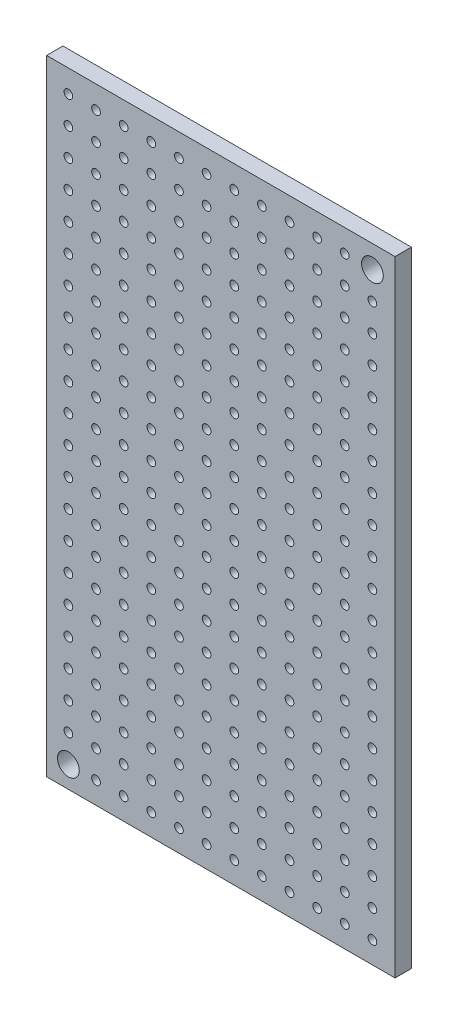
SolidWorks part; units mm, degrees
ref_plane "Front Plane" through (0, 0, 0) normal (0, 0, 1) x (1, 0, 0)
ref_plane "Top Plane" through (0, 0, 0) normal (0, 1, 0) x (1, 0, 0)
ref_plane "Right Plane" through (0, 0, 0) normal (1, 0, 0) x (0, 0, -1)
sketch "Sketch1" plane through (0, 0, 0) normal (0, 0, 1) x (1, 0, 0)
  line L1 (0, 0) -> (32.02, 0)
  line L2 (0, 0) -> (0, 57.42)
  line L3 (0, 57.42) -> (32.02, 57.42)
  line L4 (32.02, 0) -> (32.02, 57.42)
  circle A0 centre (2, 2) radius 0.4
  circle A1 centre (4.54, 2) radius 0.4
  circle A2 centre (7.08, 2) radius 0.4
  circle A3 centre (9.62, 2) radius 0.4
  circle A4 centre (12.16, 2) radius 0.4
  circle A5 centre (14.7, 2) radius 0.4
  circle A6 centre (17.24, 2) radius 0.4
  circle A7 centre (19.78, 2) radius 0.4
  circle A8 centre (22.32, 2) radius 0.4
  circle A9 centre (24.86, 2) radius 0.4
  circle A10 centre (27.4, 2) radius 0.4
  circle A11 centre (29.94, 2) radius 0.4
  circle A12 centre (2, 4.54) radius 0.4
  circle A13 centre (4.54, 4.54) radius 0.4
  circle A14 centre (7.08, 4.54) radius 0.4
  circle A15 centre (9.62, 4.54) radius 0.4
  circle A16 centre (12.16, 4.54) radius 0.4
  circle A17 centre (14.7, 4.54) radius 0.4
  circle A18 centre (17.24, 4.54) radius 0.4
  circle A19 centre (19.78, 4.54) radius 0.4
  circle A20 centre (22.32, 4.54) radius 0.4
  circle A21 centre (24.86, 4.54) radius 0.4
  circle A22 centre (27.4, 4.54) radius 0.4
  circle A23 centre (29.94, 4.54) radius 0.4
  circle A24 centre (2, 7.08) radius 0.4
  circle A25 centre (4.54, 7.08) radius 0.4
  circle A26 centre (7.08, 7.08) radius 0.4
  circle A27 centre (9.62, 7.08) radius 0.4
  circle A28 centre (12.16, 7.08) radius 0.4
  circle A29 centre (14.7, 7.08) radius 0.4
  circle A30 centre (17.24, 7.08) radius 0.4
  circle A31 centre (19.78, 7.08) radius 0.4
  circle A32 centre (22.32, 7.08) radius 0.4
  circle A33 centre (24.86, 7.08) radius 0.4
  circle A34 centre (27.4, 7.08) radius 0.4
  circle A35 centre (29.94, 7.08) radius 0.4
  circle A36 centre (2, 9.62) radius 0.4
  circle A37 centre (4.54, 9.62) radius 0.4
  circle A38 centre (7.08, 9.62) radius 0.4
  circle A39 centre (9.62, 9.62) radius 0.4
  circle A40 centre (12.16, 9.62) radius 0.4
  circle A41 centre (14.7, 9.62) radius 0.4
  circle A42 centre (17.24, 9.62) radius 0.4
  circle A43 centre (19.78, 9.62) radius 0.4
  circle A44 centre (22.32, 9.62) radius 0.4
  circle A45 centre (24.86, 9.62) radius 0.4
  circle A46 centre (27.4, 9.62) radius 0.4
  circle A47 centre (29.94, 9.62) radius 0.4
  circle A48 centre (2, 12.16) radius 0.4
  circle A49 centre (4.54, 12.16) radius 0.4
  circle A50 centre (7.08, 12.16) radius 0.4
  circle A51 centre (9.62, 12.16) radius 0.4
  circle A52 centre (12.16, 12.16) radius 0.4
  circle A53 centre (14.7, 12.16) radius 0.4
  circle A54 centre (17.24, 12.16) radius 0.4
  circle A55 centre (19.78, 12.16) radius 0.4
  circle A56 centre (22.32, 12.16) radius 0.4
  circle A57 centre (24.86, 12.16) radius 0.4
  circle A58 centre (27.4, 12.16) radius 0.4
  circle A59 centre (29.94, 12.16) radius 0.4
  circle A60 centre (2, 14.7) radius 0.4
  circle A61 centre (4.54, 14.7) radius 0.4
  circle A62 centre (7.08, 14.7) radius 0.4
  circle A63 centre (9.62, 14.7) radius 0.4
  circle A64 centre (12.16, 14.7) radius 0.4
  circle A65 centre (14.7, 14.7) radius 0.4
  circle A66 centre (17.24, 14.7) radius 0.4
  circle A67 centre (19.78, 14.7) radius 0.4
  circle A68 centre (22.32, 14.7) radius 0.4
  circle A69 centre (24.86, 14.7) radius 0.4
  circle A70 centre (27.4, 14.7) radius 0.4
  circle A71 centre (29.94, 14.7) radius 0.4
  circle A72 centre (2, 17.24) radius 0.4
  circle A73 centre (4.54, 17.24) radius 0.4
  circle A74 centre (7.08, 17.24) radius 0.4
  circle A75 centre (9.62, 17.24) radius 0.4
  circle A76 centre (12.16, 17.24) radius 0.4
  circle A77 centre (14.7, 17.24) radius 0.4
  circle A78 centre (17.24, 17.24) radius 0.4
  circle A79 centre (19.78, 17.24) radius 0.4
  circle A80 centre (22.32, 17.24) radius 0.4
  circle A81 centre (24.86, 17.24) radius 0.4
  circle A82 centre (27.4, 17.24) radius 0.4
  circle A83 centre (29.94, 17.24) radius 0.4
  circle A84 centre (2, 19.78) radius 0.4
  circle A85 centre (4.54, 19.78) radius 0.4
  circle A86 centre (7.08, 19.78) radius 0.4
  circle A87 centre (9.62, 19.78) radius 0.4
  circle A88 centre (12.16, 19.78) radius 0.4
  circle A89 centre (14.7, 19.78) radius 0.4
  circle A90 centre (17.24, 19.78) radius 0.4
  circle A91 centre (19.78, 19.78) radius 0.4
  circle A92 centre (22.32, 19.78) radius 0.4
  circle A93 centre (24.86, 19.78) radius 0.4
  circle A94 centre (27.4, 19.78) radius 0.4
  circle A95 centre (29.94, 19.78) radius 0.4
  circle A96 centre (2, 22.32) radius 0.4
  circle A97 centre (4.54, 22.32) radius 0.4
  circle A98 centre (7.08, 22.32) radius 0.4
  circle A99 centre (9.62, 22.32) radius 0.4
  circle A100 centre (12.16, 22.32) radius 0.4
  circle A101 centre (14.7, 22.32) radius 0.4
  circle A102 centre (17.24, 22.32) radius 0.4
  circle A103 centre (19.78, 22.32) radius 0.4
  circle A104 centre (22.32, 22.32) radius 0.4
  circle A105 centre (24.86, 22.32) radius 0.4
  circle A106 centre (27.4, 22.32) radius 0.4
  circle A107 centre (29.94, 22.32) radius 0.4
  circle A108 centre (2, 24.86) radius 0.4
  circle A109 centre (4.54, 24.86) radius 0.4
  circle A110 centre (7.08, 24.86) radius 0.4
  circle A111 centre (9.62, 24.86) radius 0.4
  circle A112 centre (12.16, 24.86) radius 0.4
  circle A113 centre (14.7, 24.86) radius 0.4
  circle A114 centre (17.24, 24.86) radius 0.4
  circle A115 centre (19.78, 24.86) radius 0.4
  circle A116 centre (22.32, 24.86) radius 0.4
  circle A117 centre (24.86, 24.86) radius 0.4
  circle A118 centre (27.4, 24.86) radius 0.4
  circle A119 centre (29.94, 24.86) radius 0.4
  circle A120 centre (2, 27.4) radius 0.4
  circle A121 centre (4.54, 27.4) radius 0.4
  circle A122 centre (7.08, 27.4) radius 0.4
  circle A123 centre (9.62, 27.4) radius 0.4
  circle A124 centre (12.16, 27.4) radius 0.4
  circle A125 centre (14.7, 27.4) radius 0.4
  circle A126 centre (17.24, 27.4) radius 0.4
  circle A127 centre (19.78, 27.4) radius 0.4
  circle A128 centre (22.32, 27.4) radius 0.4
  circle A129 centre (24.86, 27.4) radius 0.4
  circle A130 centre (27.4, 27.4) radius 0.4
  circle A131 centre (29.94, 27.4) radius 0.4
  circle A132 centre (2, 29.94) radius 0.4
  circle A133 centre (4.54, 29.94) radius 0.4
  circle A134 centre (7.08, 29.94) radius 0.4
  circle A135 centre (9.62, 29.94) radius 0.4
  circle A136 centre (12.16, 29.94) radius 0.4
  circle A137 centre (14.7, 29.94) radius 0.4
  circle A138 centre (17.24, 29.94) radius 0.4
  circle A139 centre (19.78, 29.94) radius 0.4
  circle A140 centre (22.32, 29.94) radius 0.4
  circle A141 centre (24.86, 29.94) radius 0.4
  circle A142 centre (27.4, 29.94) radius 0.4
  circle A143 centre (29.94, 29.94) radius 0.4
  circle A144 centre (2, 32.48) radius 0.4
  circle A145 centre (4.54, 32.48) radius 0.4
  circle A146 centre (7.08, 32.48) radius 0.4
  circle A147 centre (9.62, 32.48) radius 0.4
  circle A148 centre (12.16, 32.48) radius 0.4
  circle A149 centre (14.7, 32.48) radius 0.4
  circle A150 centre (17.24, 32.48) radius 0.4
  circle A151 centre (19.78, 32.48) radius 0.4
  circle A152 centre (22.32, 32.48) radius 0.4
  circle A153 centre (24.86, 32.48) radius 0.4
  circle A154 centre (27.4, 32.48) radius 0.4
  circle A155 centre (29.94, 32.48) radius 0.4
  circle A156 centre (2, 35.02) radius 0.4
  circle A157 centre (4.54, 35.02) radius 0.4
  circle A158 centre (7.08, 35.02) radius 0.4
  circle A159 centre (9.62, 35.02) radius 0.4
  circle A160 centre (12.16, 35.02) radius 0.4
  circle A161 centre (14.7, 35.02) radius 0.4
  circle A162 centre (17.24, 35.02) radius 0.4
  circle A163 centre (19.78, 35.02) radius 0.4
  circle A164 centre (22.32, 35.02) radius 0.4
  circle A165 centre (24.86, 35.02) radius 0.4
  circle A166 centre (27.4, 35.02) radius 0.4
  circle A167 centre (29.94, 35.02) radius 0.4
  circle A168 centre (2, 37.56) radius 0.4
  circle A169 centre (4.54, 37.56) radius 0.4
  circle A170 centre (7.08, 37.56) radius 0.4
  circle A171 centre (9.62, 37.56) radius 0.4
  circle A172 centre (12.16, 37.56) radius 0.4
  circle A173 centre (14.7, 37.56) radius 0.4
  circle A174 centre (17.24, 37.56) radius 0.4
  circle A175 centre (19.78, 37.56) radius 0.4
  circle A176 centre (22.32, 37.56) radius 0.4
  circle A177 centre (24.86, 37.56) radius 0.4
  circle A178 centre (27.4, 37.56) radius 0.4
  circle A179 centre (29.94, 37.56) radius 0.4
  circle A180 centre (2, 40.1) radius 0.4
  circle A181 centre (4.54, 40.1) radius 0.4
  circle A182 centre (7.08, 40.1) radius 0.4
  circle A183 centre (9.62, 40.1) radius 0.4
  circle A184 centre (12.16, 40.1) radius 0.4
  circle A185 centre (14.7, 40.1) radius 0.4
  circle A186 centre (17.24, 40.1) radius 0.4
  circle A187 centre (19.78, 40.1) radius 0.4
  circle A188 centre (22.32, 40.1) radius 0.4
  circle A189 centre (24.86, 40.1) radius 0.4
  circle A190 centre (27.4, 40.1) radius 0.4
  circle A191 centre (29.94, 40.1) radius 0.4
  circle A192 centre (2, 42.64) radius 0.4
  circle A193 centre (4.54, 42.64) radius 0.4
  circle A194 centre (7.08, 42.64) radius 0.4
  circle A195 centre (9.62, 42.64) radius 0.4
  circle A196 centre (12.16, 42.64) radius 0.4
  circle A197 centre (14.7, 42.64) radius 0.4
  circle A198 centre (17.24, 42.64) radius 0.4
  circle A199 centre (19.78, 42.64) radius 0.4
  circle A200 centre (22.32, 42.64) radius 0.4
  circle A201 centre (24.86, 42.64) radius 0.4
  circle A202 centre (27.4, 42.64) radius 0.4
  circle A203 centre (29.94, 42.64) radius 0.4
  circle A204 centre (2, 45.18) radius 0.4
  circle A205 centre (4.54, 45.18) radius 0.4
  circle A206 centre (7.08, 45.18) radius 0.4
  circle A207 centre (9.62, 45.18) radius 0.4
  circle A208 centre (12.16, 45.18) radius 0.4
  circle A209 centre (14.7, 45.18) radius 0.4
  circle A210 centre (17.24, 45.18) radius 0.4
  circle A211 centre (19.78, 45.18) radius 0.4
  circle A212 centre (22.32, 45.18) radius 0.4
  circle A213 centre (24.86, 45.18) radius 0.4
  circle A214 centre (27.4, 45.18) radius 0.4
  circle A215 centre (29.94, 45.18) radius 0.4
  circle A216 centre (2, 47.72) radius 0.4
  circle A217 centre (4.54, 47.72) radius 0.4
  circle A218 centre (7.08, 47.72) radius 0.4
  circle A219 centre (9.62, 47.72) radius 0.4
  circle A220 centre (12.16, 47.72) radius 0.4
  circle A221 centre (14.7, 47.72) radius 0.4
  circle A222 centre (17.24, 47.72) radius 0.4
  circle A223 centre (19.78, 47.72) radius 0.4
  circle A224 centre (22.32, 47.72) radius 0.4
  circle A225 centre (24.86, 47.72) radius 0.4
  circle A226 centre (27.4, 47.72) radius 0.4
  circle A227 centre (29.94, 47.72) radius 0.4
  circle A228 centre (2, 50.26) radius 0.4
  circle A229 centre (4.54, 50.26) radius 0.4
  circle A230 centre (7.08, 50.26) radius 0.4
  circle A231 centre (9.62, 50.26) radius 0.4
  circle A232 centre (12.16, 50.26) radius 0.4
  circle A233 centre (14.7, 50.26) radius 0.4
  circle A234 centre (17.24, 50.26) radius 0.4
  circle A235 centre (19.78, 50.26) radius 0.4
  circle A236 centre (22.32, 50.26) radius 0.4
  circle A237 centre (24.86, 50.26) radius 0.4
  circle A238 centre (27.4, 50.26) radius 0.4
  circle A239 centre (29.94, 50.26) radius 0.4
  circle A240 centre (2, 52.8) radius 0.4
  circle A241 centre (4.54, 52.8) radius 0.4
  circle A242 centre (7.08, 52.8) radius 0.4
  circle A243 centre (9.62, 52.8) radius 0.4
  circle A244 centre (12.16, 52.8) radius 0.4
  circle A245 centre (14.7, 52.8) radius 0.4
  circle A246 centre (17.24, 52.8) radius 0.4
  circle A247 centre (19.78, 52.8) radius 0.4
  circle A248 centre (22.32, 52.8) radius 0.4
  circle A249 centre (24.86, 52.8) radius 0.4
  circle A250 centre (27.4, 52.8) radius 0.4
  circle A251 centre (29.94, 52.8) radius 0.4
  circle A252 centre (2, 55.34) radius 0.4
  circle A253 centre (4.54, 55.34) radius 0.4
  circle A254 centre (7.08, 55.34) radius 0.4
  circle A255 centre (9.62, 55.34) radius 0.4
  circle A256 centre (12.16, 55.34) radius 0.4
  circle A257 centre (14.7, 55.34) radius 0.4
  circle A258 centre (17.24, 55.34) radius 0.4
  circle A259 centre (19.78, 55.34) radius 0.4
  circle A260 centre (22.32, 55.34) radius 0.4
  circle A261 centre (24.86, 55.34) radius 0.4
  circle A262 centre (27.4, 55.34) radius 0.4
  circle A263 centre (29.94, 55.34) radius 0.4
  dimension "D3" = 0.8
  dimension "D1" = 32.02
  dimension "D2" = 57.42
  dimension "D4" = 2
  dimension "D7" = 2
  dimension "D5" = 12
  dimension "D6" = 22
extrude "Boss-Extrude1" add sketch "Sketch1" along normal blind 1.5
sketch "Sketch2" plane through (0, 0, 1.5) normal (0, 0, 1) x (1, 0, 0)
  circle A0 centre (2, 2) radius 1
  circle A1 centre (29.94, 55.34) radius 1
  circle A2 centre (29.94, 55.34) radius 0.4 construction
  dimension "D1" = 2
  dimension "D2" = 2
extrude "Cut-Extrude1" cut sketch "Sketch2" against normal blind 5
equation "\"D2@Sketch1\"=23*2.54-1"
equation "\"D7@Sketch1\"=\"D4@Sketch1\""
equation "\"D1@Sketch1\"=13*2.54-1"
equation "\"D4@Sketch1\"=2.5 -.5"
